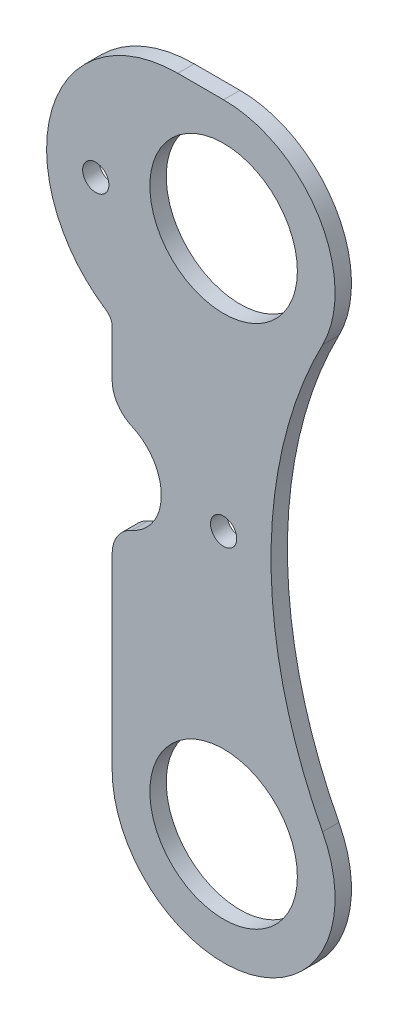
SolidWorks part; units mm, degrees
material "6061 Alloy"
ref_plane "Front Plane" through (0, 0, 0) normal (0, 0, 1) x (1, 0, 0)
ref_plane "Top Plane" through (0, 0, 0) normal (0, 1, 0) x (1, 0, 0)
ref_plane "Right Plane" through (0, 0, 0) normal (1, 0, 0) x (0, 0, -1)
sketch "Sketch1" plane through (0, 0, 0) normal (0, 0, 1) x (1, 0, 0)
  line L0 (0, 0) -> (0, -101.6) construction
  line L1 (21.59, -120.5575) -> (-21.59, -120.5575) construction
  line L2 (-8.89, 25.4) -> (8.89, 25.4)
  line L3 (-21.59, 12.7) -> (-21.59, -117.7751)
  line L5 (21.59, 12.7) -> (21.59, -117.7751)
  line L9 (-23.3829, -122.6853) -> (-33.2033, -134.3394)
  line L10 (-36.322, 25.4) -> (20.828, 25.4) construction
  line L11 (-36.322, 25.4) -> (-36.322, -203.2) construction
  line L12 (-36.322, -203.2) -> (20.828, -203.2) construction
  line L13 (20.828, 25.4) -> (20.828, -203.2) construction
  line L15 (-7.9527, -155.6168) -> (19.7971, -122.6853)
  line L16 (-32.4392, -143.2871) -> (-16.9004, -156.3809)
  circle A0 centre (0, 0) radius 38.1 construction
  circle A1 centre (0, -101.6) radius 38.1 construction
  circle A2 centre (0, 0) radius 14.2875
  circle A3 centre (0, -101.6) radius 14.2875
  arc A6 (8.89, 25.4) -> (21.59, 12.7) centre (8.89, 12.7) cw
  arc A7 (-8.89, 25.4) -> (-21.59, 12.7) centre (-8.89, 12.7) ccw
  circle A10 centre (-18.5321, -142.5501) radius 2.54
  arc A13 (-23.3829, -122.6853) -> (-21.59, -117.7751) centre (-29.21, -117.7751) ccw
  arc A14 (19.7971, -122.6853) -> (21.59, -117.7751) centre (13.97, -117.7751) ccw
  arc A15 (-16.9004, -156.3809) -> (-7.9527, -155.6168) centre (-12.8086, -151.525) ccw
  arc A16 (-33.2033, -134.3394) -> (-32.4392, -143.2871) centre (-28.3474, -138.4312) ccw
  circle A17 centre (0, -50.8) radius 2.54
  point P13 (-192.705, 39.2708)
  point P20 (21.59, 25.4)
  point P23 (-21.59, 25.4)
  point P31 (-36.322, -138.0404)
  dimension "D2" = 76.2
  dimension "D3" = 76.2
  dimension "D4" = 28.575
  dimension "D5" = 28.575
  dimension "D10" = 228.6
  dimension "D11" = 36.322
  dimension "D13" = 5.08
  dimension "D19" = 6.35
  dimension "D20" = 7.62
  dimension "D21" = 12.7
  dimension "D22" = 5.08
  dimension "D1" = 101.6
  dimension "D6" = 43.18
  dimension "D7" = 21.59
  dimension "D8" = 25.4
  dimension "D9" = 57.15
  dimension "D12" = 25.4
  dimension "D14" = 33.02
  dimension "D15" = 16.51
  dimension "D16" = 21.59
  dimension "D17" = 9.525
  dimension "D18" = 18.9575
extrude "Boss-Extrude1" add sketch "Sketch1" along normal blind 3.175
sketch "Sketch2" plane through (0, 0, 0) normal (0, 0, 1) x (1, 0, 0)
  line L0 (-21.59, -41.275) -> (-21.59, -60.325)
  line L1 (0, 0) -> (0, -101.6) construction
  line L4 (21.59, -117.7751) -> (21.59, 12.7) construction
  line L5 (-21.59, -50.8) -> (97.79, -50.8) construction
  line L6 (-21.59, 12.7) -> (-21.59, -117.7751) construction
  line L7 (0, 0) -> (-39.9512, 0) construction
  line L9 (16.51, -115.5122) -> (-17.5013, -155.8745)
  line L10 (-32.4392, -143.2871) -> (-16.9004, -156.3809) construction
  line L11 (-7.9527, -155.6168) -> (19.7971, -122.6853) construction
  line L13 (27.94, -121.6567) -> (-7.6203, -163.8572)
  line L14 (-7.6203, -163.8572) -> (-17.5013, -155.8745)
  line L15 (27.94, -121.6567) -> (27.94, 0)
  line L16 (27.94, 0) -> (21.59, 0)
  arc A1 (19.1591, -91.6472) -> (19.1591, -9.9528) centre (97.79, -50.8) cw
  arc A2 (-21.59, -60.325) -> (-21.59, -41.275) centre (-21.59, -50.8) ccw
  arc A3 (21.59, 0) -> (19.1591, -9.9528) centre (0, 0) cw
  arc A4 (21.59, -101.6) -> (19.1591, -91.6472) centre (0, -101.6) ccw
  arc A5 (21.59, -101.6) -> (16.51, -115.5122) centre (0, -101.6) cw
  dimension "D2" = 12.7
  dimension "D3" = 50.8
  dimension "D4" = 6.35
  dimension "D1" = 76.2
  dimension "D5" = 19.05
extrude "Cut-Extrude1" cut sketch "Sketch2" along normal through all contours A1 A3 L16 L15 L13 L14 L9 A5 A4 | L0 A2
sketch "Sketch3" plane through (0, 0, 3.175) normal (0, 0, 1) x (1, 0, 0)
  line L0 (-27.3514, -127.3948) -> (-36.0255, -137.6886)
  line L3 (-27.3514, -127.3948) -> (-7.5576, -144.074)
  line L4 (-23.3829, -122.6853) -> (-33.2033, -134.3394) construction
  line L5 (16.51, -115.5122) -> (-17.5013, -155.8745) construction
  line L7 (-35.4064, -144.9387) -> (-24.4031, -154.2106)
  line L8 (-23.3829, -122.6853) -> (-33.2033, -134.3394) construction
  line L9 (-7.5576, -144.074) -> (-15.4554, -153.4465)
  line L10 (-32.4392, -143.2871) -> (-17.5013, -155.8745) construction
  circle A2 centre (-18.5321, -142.5501) radius 2.54
  circle A3 centre (-18.5321, -142.5501) radius 2.54 construction
  arc A5 (-36.0255, -137.6886) -> (-35.4064, -144.9387) centre (-32.0909, -141.0041) ccw
  arc A6 (-24.4031, -154.2106) -> (-15.4554, -153.4465) centre (-20.3113, -149.3547) ccw
  dimension "D2" = 6.35
  dimension "D3" = 5.1453
  dimension "D1" = 3.175
fillet "Fillet3" radius 6.35 2 edges at (-21.59, -60.325, 1.5875) (-21.59, -41.275, 1.5875)
extrude "Boss-Extrude3" add sketch "Sketch3" against normal blind 3.175
sketch "Sketch6" plane through (0, 0, 3.175) normal (0, 0, 1) x (1, 0, 0)
  line L0 (-35.4064, -144.9387) -> (-63.6204, -121.1641)
  line L1 (-63.6204, -121.1641) -> (-51.345, -106.5965)
  line L2 (-51.345, -106.5965) -> (-27.0656, -127.0555)
  line L4 (-35.4064, -144.9387) -> (-24.4031, -154.2106) construction
  line L5 (-23.3829, -122.6853) -> (-36.0255, -137.6886) construction
  line L6 (-35.4064, -144.9387) -> (-27.0656, -127.0555)
  circle A0 centre (-52.6268, -117.9721) radius 2.54
  dimension "D4" = 5.08
  dimension "D1" = 31.75
  dimension "D2" = 9.525
  dimension "1" = 19.05
  dimension "D3" = 6.35
extrude "Boss-Extrude4" add sketch "Sketch6" against normal blind 3.175
fillet "Fillet2" radius 6.35 3 edges at (-63.6204, -121.1641, 1.5875) (-51.345, -106.5965, 1.5875) (-27.0656, -127.0555, 1.5875)
sketch "Sketch7" plane through (0, 0, 3.175) normal (0, 0, 1) x (1, 0, 0)
  line L0 (-21.59, 12.7) -> (-21.59, -36.2503) construction
  line L1 (21.59, 0) -> (21.59, 12.7) construction
  line L2 (-21.59, 0) -> (21.59, 0) construction
  line L3 (-21.59, 0) -> (-21.59, 31.75)
  line L4 (-21.59, 31.75) -> (21.59, 31.75)
  line L5 (21.59, 31.75) -> (21.59, 0)
  line L6 (8.89, 25.4) -> (-8.89, 25.4) construction
  arc A0 (-21.59, 0) -> (21.59, 0) centre (0, 0) cw
  dimension "D1" = 6.35
extrude "Cut-Extrude2" cut sketch "Sketch7" against normal through all
sketch "Sketch10" plane through (0, 0, 3.175) normal (0, 0, 1) x (1, 0, 0)
  line L0 (16.51, -115.5122) -> (-17.5013, -155.8745) construction
  line L1 (-18.1519, -155.3263) -> (-17.3615, -157.512)
  line L2 (-17.3615, -157.512) -> (-14.3757, -156.4323)
  line L3 (-14.3757, -156.4323) -> (-15.4554, -153.4465)
  line L5 (-18.1519, -155.3263) -> (-17.5013, -155.8745) construction
  circle A0 centre (-20.3113, -149.3547) radius 6.35 construction
  arc A1 (-24.4031, -154.2106) -> (-18.1519, -155.3263) centre (-20.3113, -149.3547) ccw construction
  arc A2 (-18.1519, -155.3263) -> (-15.4554, -153.4465) centre (-20.3113, -149.3547) ccw
  dimension "D1" = 3.175
  dimension "D2" = 30
extrude "Cut-Extrude3" cut sketch "Sketch10" against normal through all
sketch "Sketch12" plane through (0, 0, 3.175) normal (0, 0, 1) x (1, 0, 0)
  line L0 (-21.59, -65.3497) -> (-21.59, -117.7751) construction
  line L1 (-21.59, -101.6) -> (-72.39, -101.6)
  line L2 (-72.39, -101.6) -> (-72.39, -165.1)
  line L3 (-72.39, -165.1) -> (16.51, -165.1)
  line L4 (16.51, -165.1) -> (16.51, -115.5122)
  arc A2 (16.51, -115.5122) -> (-21.59, -101.6) centre (0, -101.6) cw
  dimension "D1" = 63.5
  dimension "D2" = 88.9
extrude "Cut-Extrude4" cut sketch "Sketch12" against normal through all
sketch "Sketch15" plane through (0, 0, 3.175) normal (0, 0, 1) x (1, 0, 0)
  line L0 (-21.59, 0) -> (-21.59, -36.2503) construction
  line L5 (-21.59, -29.21) -> (-21.59, 0)
  line L7 (0, 21.59) -> (-16.6076, 6.9565)
  line L8 (-16.6076, 6.9565) -> (-12.5785, -28.9408)
  line L9 (-8.89, 21.59) -> (0, 21.59)
  arc A0 (-12.5785, -28.9408) -> (-34.29, -3.81) centre (-8.89, -3.81) cw
  arc A1 (-8.89, 21.59) -> (-34.29, -3.81) centre (-8.89, -3.81) ccw
  circle A2 centre (-24.765, -3.81) radius 2.54
  arc A3 (19.1591, -9.9528) -> (-21.59, 0) centre (0, 0) ccw construction
  arc M10 (19.1591, -9.9528) -> (-21.59, 0) centre (0, 0) ccw
  line M11 (-21.59, 0) -> (-21.59, -36.2503)
  dimension "D1" = 12.7
  dimension "D4" = 3.175
  dimension "D3" = 5.08
  dimension "D2" = 25.4
extrude "Boss-Extrude8" add sketch "Sketch15" against normal blind 3.175 contours L9 A1 A0 A2 M11 M10
fillet "Fillet4" radius 2.54 1 edges at (-21.59, -25.807, 1.5875)
